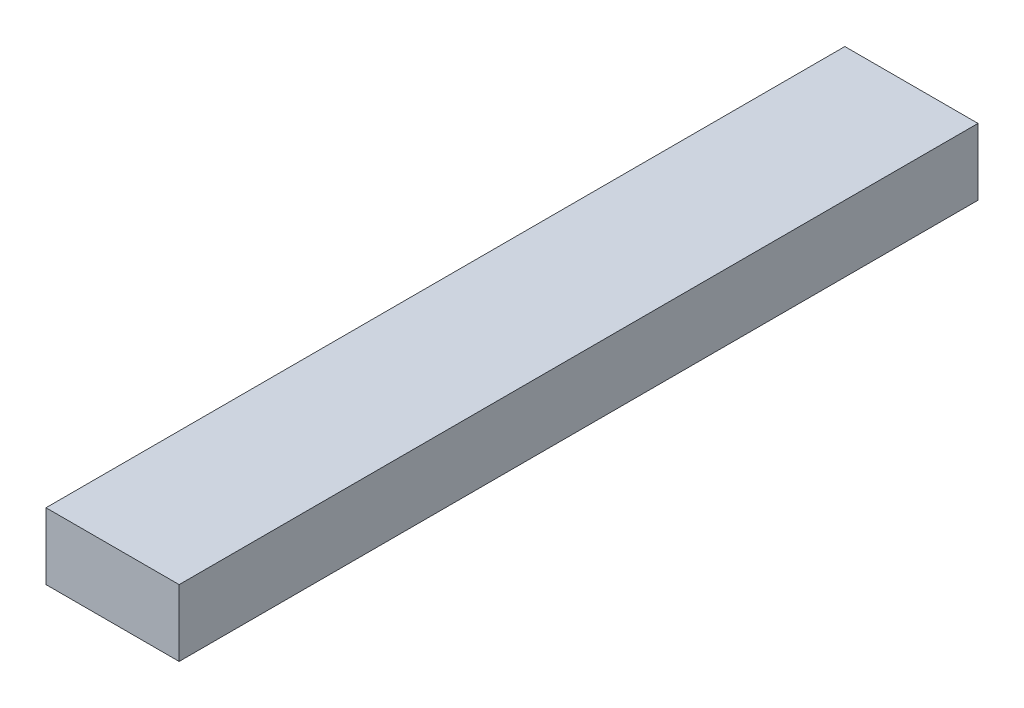
SolidWorks part; units mm, degrees
ref_plane "Front Plane" through (0, 0, 0) normal (0, 0, 1) x (1, 0, 0)
ref_plane "Top Plane" through (0, 0, 0) normal (0, 1, 0) x (1, 0, 0)
ref_plane "Right Plane" through (0, 0, 0) normal (1, 0, 0) x (0, 0, -1)
sketch "Sketch1" plane through (0, 0, 0) normal (0, 0, 1) x (1, 0, 0)
  line L1 (-50.8, -25.4) -> (50.8, -25.4)
  line L2 (-50.8, -25.4) -> (-50.8, 25.4)
  line L3 (-50.8, 25.4) -> (50.8, 25.4)
  line L4 (50.8, -25.4) -> (50.8, 25.4)
  line L5 (-50.8, -25.4) -> (50.8, 25.4) construction
  line L6 (-50.8, 25.4) -> (50.8, -25.4) construction
  point P0 (0, 0)
  dimension "D1" = 50.8
  dimension "D2" = 101.6
extrude "Boss-Extrude1" add sketch "Sketch1" along normal blind 609.6
